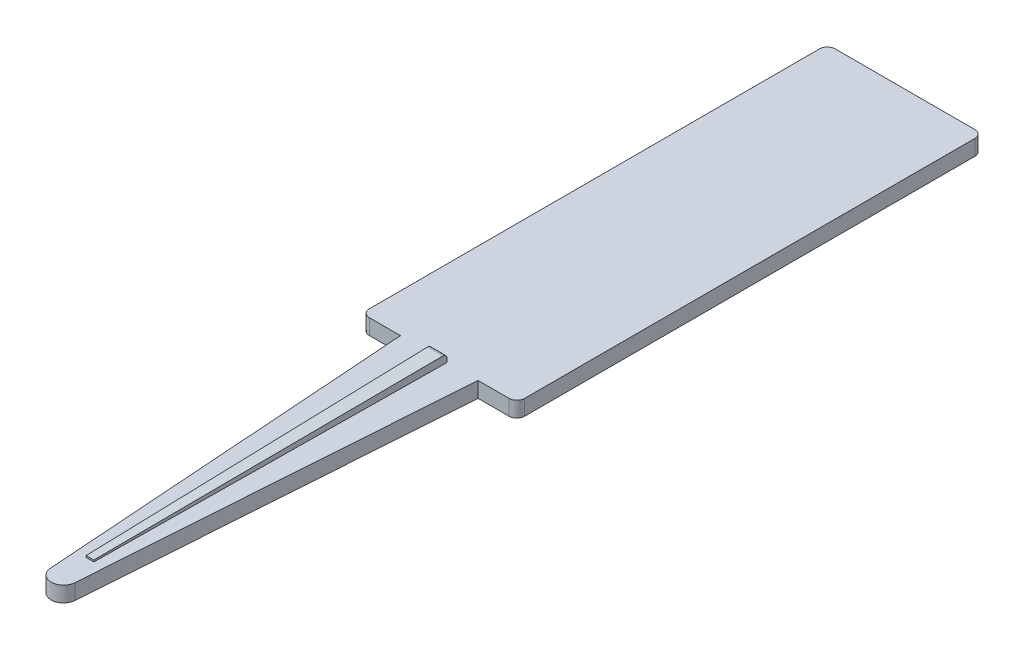
SolidWorks part; units mm, degrees
ref_plane "Front Plane" through (0, 0, 0) normal (0, 0, 1) x (1, 0, 0)
ref_plane "Top Plane" through (0, 0, 0) normal (0, 1, 0) x (1, 0, 0)
ref_plane "Right Plane" through (0, 0, 0) normal (1, 0, 0) x (0, 0, -1)
sketch "Sketch1" plane through (0, 0, 0) normal (0, 1, 0) x (1, 0, 0)
  line L0 (10, -60) -> (10, -160) construction
  line L1 (0, 0) -> (20, 0)
  line L2 (0, 0) -> (0, -60)
  line L3 (0, -60) -> (5, -60)
  line L4 (20, 0) -> (20, -60)
  line L5 (8.4, -108.5082) -> (5, -60)
  line L7 (10, -110) -> (10, -109.4336) construction
  line L8 (15, -60) -> (20, -60)
  line L10 (11.6, -108.5082) -> (15, -60)
  arc A0 (8.4, -108.5082) -> (11.6, -108.5082) centre (10, -108.3961) ccw
  point P11 (0, 0)
  dimension "D1" = 20
  dimension "D2" = 60
  dimension "D3" = 3.2
  dimension "D4" = 5
  dimension "D5" = 5
  dimension "D6" = 50
  dimension "D7" = 5
  dimension "D8" = 10
extrude "Boss-Extrude1" add sketch "Sketch1" along normal blind 2
fillet "Fillet2" radius 1 1 edges at (0, 1, 0)
fillet "Fillet3" radius 1 1 edges at (20, 1, 60)
fillet "Fillet4" radius 1 1 edges at (20, 1, 0)
fillet "Fillet5" radius 1 1 edges at (0, 1, 60)
sketch "Sketch5" plane through (0, 2, 0) normal (0, 1, 0) x (1, 0, 0)
  line L0 (5, -60) -> (15, -60) construction
  line L1 (10, -60) -> (10, -110) construction
  line L2 (10.5, -105) -> (9.5, -105) construction
  line L3 (11, -60) -> (9, -60)
  line L4 (10, -105) -> (10, -73.6816) construction
  line L5 (11, -60) -> (10.5, -105)
  line L6 (10.5, -105) -> (9.5, -105)
  line L7 (9.5, -105) -> (9, -60)
  arc A1 (8.4, -108.5082) -> (11.6, -108.5082) centre (10, -108.3961) ccw construction
  dimension "D1" = 1
  dimension "D2" = 2
  dimension "D3" = 5
extrude "Boss-Extrude2" add sketch "Sketch5" along normal blind 1
draft "Draft1" type of draft neutral plane draft angle 1 faces to draft 1 face at (10, 3, 82.5) neutral plane through (11, 3, 60) neutral plane normal (0, 0, -1) reverse direction yes parameters "D1"=1
fillet "Fillet7" radius 0.5 1 edges at (10, 3, 60)
